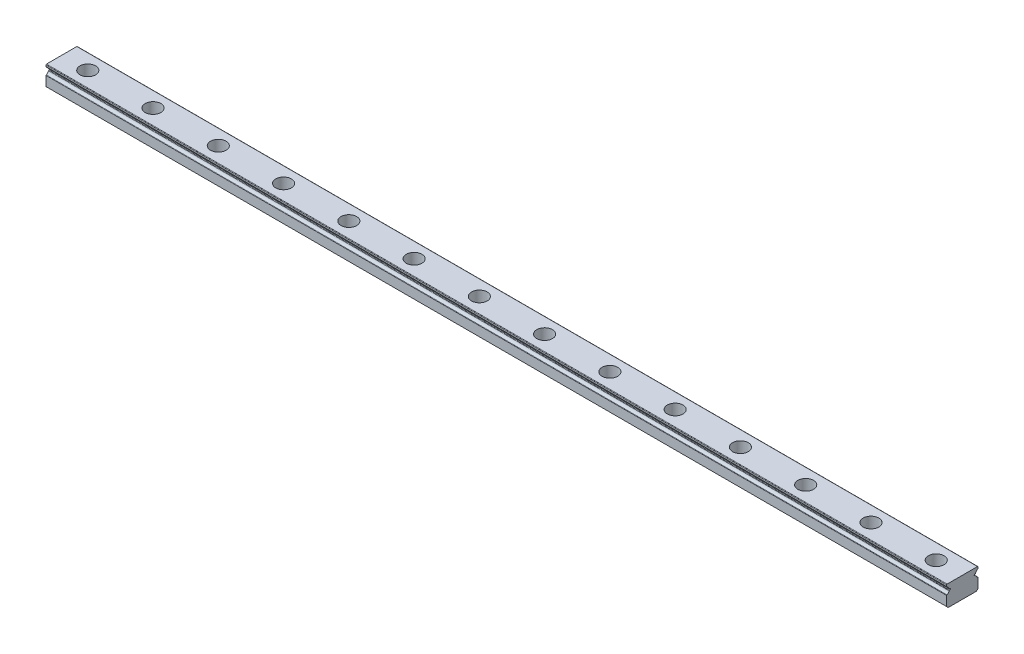
SolidWorks part; units mm, degrees
ref_plane "前视基准面" through (0, 0, 0) normal (0, 0, 1) x (1, 0, 0)
ref_plane "上视基准面" through (0, 0, 0) normal (0, 1, 0) x (1, 0, 0)
ref_plane "右视基准面" through (0, 0, 0) normal (1, 0, 0) x (0, 0, -1)
other "Configuration Table"
ref_plane "基准面1" through (0, 4, 0) normal (0, 1, 0) x (1, 0, 0)
sketch "草图1" plane through (0, 4, 0) normal (0, 1, 0) x (1, 0, 0)
  line L0 (172.5, -6) -> (172.5, 6)
  line L1 (172.5, 6) -> (-172.5, 6)
  line L2 (-172.5, 6) -> (-172.5, -6)
  line L3 (-172.5, -6) -> (172.5, -6)
extrude "凸台-拉伸1" add sketch "草图1" against normal blind 8
sketch "草图2" plane through (172.5, 0, 0) normal (1, 0, 0) x (0, 0, -1)
  line L0 (6, 1.51) -> (6, 2.01)
  line L1 (6, 2.01) -> (4.8, 2.01)
  line L2 (4.8, 1.51) -> (6, 1.51)
  arc A0 (4.8, 2.01) -> (4.8, 1.51) centre (4.8, 1.76) ccw
extrude "切除-拉伸1" cut sketch "草图2" against normal through all
sketch "草图3" plane through (172.5, 0, 0) normal (1, 0, 0) x (0, 0, -1)
  line L0 (6, 2.01) -> (6, 3.1111)
  line L1 (5.04, 2.01) -> (6, 2.01)
  arc A0 (6, 3.1111) -> (5.04, 2.01) centre (6.4382, 1.76) ccw
extrude "切除-拉伸2" cut sketch "草图3" against normal through all
sketch "草图4" plane through (172.5, 0, 0) normal (1, 0, 0) x (0, 0, -1)
  line L0 (6, 1.51) -> (5.04, 1.51)
  line L1 (6, 0.4089) -> (6, 1.51)
  arc A0 (5.04, 1.51) -> (6, 0.4089) centre (6.4382, 1.76) ccw
extrude "切除-拉伸3" cut sketch "草图4" against normal through all
sketch "草图5" plane through (172.5, 0, 0) normal (1, 0, 0) x (0, 0, -1)
  line L0 (-6, 2.01) -> (-6, 1.51)
  line L1 (-6, 1.51) -> (-4.8, 1.51)
  line L2 (-4.8, 2.01) -> (-6, 2.01)
  arc A0 (-4.8, 1.51) -> (-4.8, 2.01) centre (-4.8, 1.76) ccw
extrude "切除-拉伸4" cut sketch "草图5" against normal through all
sketch "草图6" plane through (172.5, 0, 0) normal (1, 0, 0) x (0, 0, -1)
  line L0 (-6, 1.51) -> (-6, 0.4089)
  line L1 (-5.04, 1.51) -> (-6, 1.51)
  arc A0 (-6, 0.4089) -> (-5.04, 1.51) centre (-6.4382, 1.76) ccw
extrude "切除-拉伸5" cut sketch "草图6" against normal through all
sketch "草图7" plane through (172.5, 0, 0) normal (1, 0, 0) x (0, 0, -1)
  line L0 (-6, 2.01) -> (-5.04, 2.01)
  line L1 (-6, 3.1111) -> (-6, 2.01)
  arc A0 (-5.04, 2.01) -> (-6, 3.1111) centre (-6.4382, 1.76) ccw
extrude "切除-拉伸6" cut sketch "草图7" against normal through all
hole_wizard "M3 六角头机械螺钉的柱形沉头孔1" positions "草图9" profile "草图8" counterbore size "M3" standard "ANSI Metric"
sketch "草图9" plane through (0, 4, 0) normal (0, 1, 0) x (1, 0, 0)
  point P0 (-162.5, 0)
  point P1 (-137.5, 0)
  point P2 (-112.5, 0)
  point P3 (-87.5, 0)
  point P4 (-62.5, 0)
  point P5 (-37.5, 0)
  point P6 (-12.5, 0)
  point P7 (12.5, 0)
  point P8 (37.5, 0)
  point P9 (62.5, 0)
  point P10 (87.5, 0)
  point P11 (112.5, 0)
  point P12 (137.5, 0)
  point P13 (162.5, 0)
sketch "草图8" plane through (-162.5, 4, 0) normal (1, 0, 0) x (0, 0, 1)
  line L0 (0, 0) -> (0, 8)
  line L1 (0, 8) -> (1.75, 8)
  line L3 (1.75, 8) -> (1.75, 4.5)
  line L4 (1.75, 4.5) -> (2.9999, 4.5)
  line L5 (2.9999, 4.5) -> (2.9999, 0)
  line L7 (2.9999, 0) -> (0, 0)
  line L11 (0, -6.35) -> (0, 107.95) construction
  dimension "通孔孔直径" = 3.5
  dimension "通孔孔深度" = 8
  dimension "柱形沉头孔直径" = 5.9999
  dimension "柱形沉头孔深度" = 4.5
chamfer "倒角1" distance 0.6 angle 45 2 edges at (0, -4, -6) (0, -4, 6)
fillet "圆角1" radius 0.2 10 edges at (0, 3.1111, -6) (0, 1.51, -5.04) (0, 4, -6) (0, 1.51, 5.04) (0, 2.01, -5.04) (0, 2.01, 5.04) (0, 4, 6) (0, 3.1111, 6) (0, 0.4089, -6) (0, 0.4089, 6)
